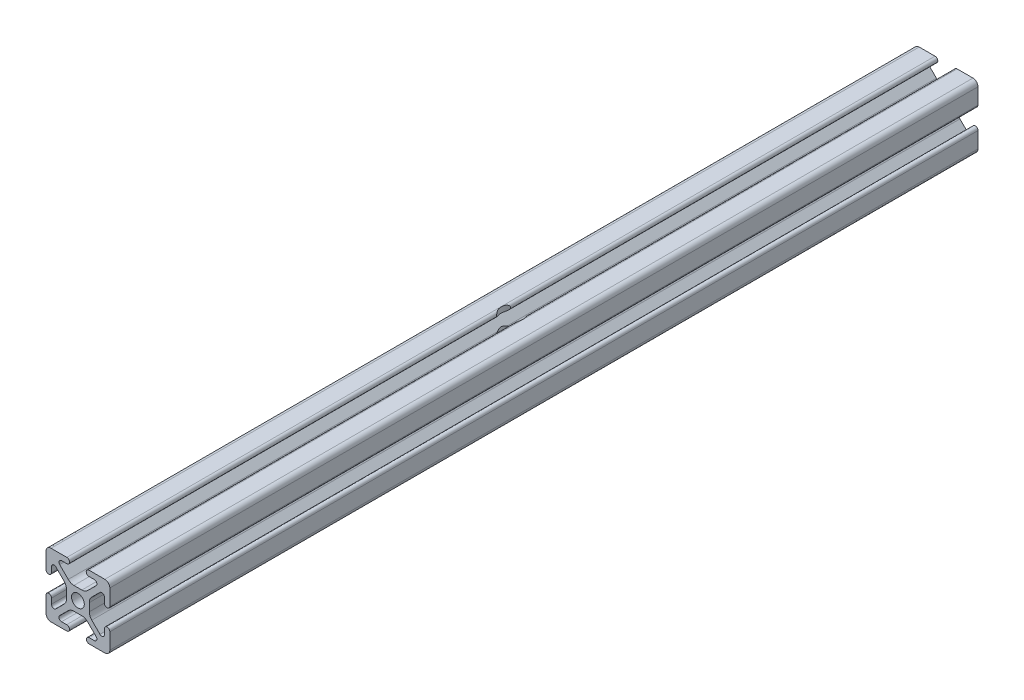
SolidWorks part; units mm, degrees
material "1060 Alloy"
ref_plane "Front Plane" through (0, 0, 0) normal (0, 0, 1) x (1, 0, 0)
ref_plane "Top Plane" through (0, 0, 0) normal (0, 1, 0) x (1, 0, 0)
ref_plane "Right Plane" through (0, 0, 0) normal (1, 0, 0) x (0, 0, -1)
ref_plane "Plane1" through (0, 0, -500) normal (0, 0, -1) x (-1, 0, 0)
sketch "Sketch1" plane through (0, 0, -500) normal (0, 0, -1) x (-1, 0, 0)
  line L0 (12.5, 4.32) -> (12.5, 10.5371)
  line L1 (10.5371, 12.5) -> (4.32, 12.5)
  line L2 (4.32, 10.36) -> (6.42, 10.36)
  line L3 (7.1337, 8.6353) -> (3.7953, 5.3018)
  line L4 (1.5554, 4.375) -> (-1.5554, 4.375)
  line L5 (-3.7953, 5.3018) -> (-7.1337, 8.6353)
  line L6 (-6.42, 10.36) -> (-4.32, 10.36)
  line L7 (-4.32, 12.5) -> (-10.5371, 12.5)
  line L8 (-12.5, 10.5371) -> (-12.5, 4.32)
  line L9 (-10.36, 4.32) -> (-10.36, 6.3969)
  line L10 (-8.6363, 7.1116) -> (-5.4322, 3.9121)
  line L11 (-4.455, 1.5554) -> (-4.455, -1.5554)
  line L12 (-5.4322, -3.9121) -> (-8.6363, -7.1116)
  line L13 (-10.36, -6.3969) -> (-10.36, -4.32)
  line L14 (-12.5, -4.32) -> (-12.5, -10.5371)
  line L15 (-10.5371, -12.5) -> (-4.3879, -12.5)
  line L16 (-4.3879, -10.36) -> (-6.42, -10.36)
  line L17 (-7.1337, -8.6353) -> (-3.7953, -5.3018)
  line L18 (-1.5554, -4.375) -> (1.5554, -4.375)
  line L19 (3.7953, -5.3018) -> (7.1337, -8.6353)
  line L20 (6.42, -10.36) -> (4.3879, -10.36)
  line L21 (4.3879, -12.5) -> (10.5371, -12.5)
  line L22 (12.5, -10.5371) -> (12.5, -4.32)
  line L23 (10.36, -4.32) -> (10.36, -6.3969)
  line L24 (8.6363, -7.1116) -> (5.4322, -3.9121)
  line L25 (4.455, -1.5554) -> (4.455, 1.5554)
  line L26 (5.4322, 3.9121) -> (8.6363, 7.1116)
  line L27 (10.36, 6.3969) -> (10.36, 4.32)
  circle A0 centre (0, 0) radius 2.5
  arc A1 (12.5, 10.5371) -> (10.5371, 12.5) centre (10.5371, 10.5371) ccw
  arc A2 (4.32, 12.5) -> (4.32, 10.36) centre (4.32, 11.43) ccw
  arc A3 (6.42, 10.36) -> (7.1337, 8.6353) centre (6.42, 9.35) cw
  arc A4 (3.7953, 5.3018) -> (1.5554, 4.375) centre (1.5554, 7.545) cw
  arc A5 (-1.5554, 4.375) -> (-3.7953, 5.3018) centre (-1.5554, 7.545) cw
  arc A6 (-7.1337, 8.6353) -> (-6.42, 10.36) centre (-6.42, 9.35) cw
  arc A7 (-4.32, 10.36) -> (-4.32, 12.5) centre (-4.32, 11.43) ccw
  arc A8 (-10.5371, 12.5) -> (-12.5, 10.5371) centre (-10.5371, 10.5371) ccw
  arc A9 (-12.5, 4.32) -> (-10.36, 4.32) centre (-11.43, 4.32) ccw
  arc A10 (-10.36, 6.3969) -> (-8.6363, 7.1116) centre (-9.35, 6.3969) cw
  arc A11 (-5.4322, 3.9121) -> (-4.455, 1.5554) centre (-7.7855, 1.5554) cw
  arc A12 (-4.455, -1.5554) -> (-5.4322, -3.9121) centre (-7.7855, -1.5554) cw
  arc A13 (-8.6363, -7.1116) -> (-10.36, -6.3969) centre (-9.35, -6.3969) cw
  arc A14 (-10.36, -4.32) -> (-12.5, -4.32) centre (-11.43, -4.32) ccw
  arc A15 (-12.5, -10.5371) -> (-10.5371, -12.5) centre (-10.5371, -10.5371) ccw
  arc A16 (-4.3879, -12.5) -> (-4.3879, -10.36) centre (-4.3879, -11.43) ccw
  arc A17 (-6.42, -10.36) -> (-7.1337, -8.6353) centre (-6.42, -9.35) cw
  arc A18 (-3.7953, -5.3018) -> (-1.5554, -4.375) centre (-1.5554, -7.545) cw
  arc A19 (1.5554, -4.375) -> (3.7953, -5.3018) centre (1.5554, -7.545) cw
  arc A20 (7.1337, -8.6353) -> (6.42, -10.36) centre (6.42, -9.35) cw
  arc A21 (4.3879, -10.36) -> (4.3879, -12.5) centre (4.3879, -11.43) ccw
  arc A22 (10.5371, -12.5) -> (12.5, -10.5371) centre (10.5371, -10.5371) ccw
  arc A23 (12.5, -4.32) -> (10.36, -4.32) centre (11.43, -4.32) ccw
  arc A24 (10.36, -6.3969) -> (8.6363, -7.1116) centre (9.35, -6.3969) cw
  arc A25 (5.4322, -3.9121) -> (4.455, -1.5554) centre (7.7855, -1.5554) cw
  arc A26 (4.455, 1.5554) -> (5.4322, 3.9121) centre (7.7855, 1.5554) cw
  arc A27 (8.6363, 7.1116) -> (10.36, 6.3969) centre (9.35, 6.3969) cw
  arc A28 (10.36, 4.32) -> (12.5, 4.32) centre (11.43, 4.32) ccw
extrude "Boss-Extrude1" add sketch "Sketch1" against normal blind 340
sketch "Sketch2" plane through (0, 0, 0) normal (0, 1, 0) x (1, 0, 0)
  line L0 (0, 500) -> (0, 160) construction
  line L1 (-1.5554, 500) -> (1.5554, 500) construction
  line L2 (-1.5554, 160) -> (1.5554, 160) construction
  circle A0 centre (0, 330) radius 4.25
  dimension "D1" = 8.5
extrude "Cut-Extrude1" cut sketch "Sketch2" against normal through all and the other way through all
